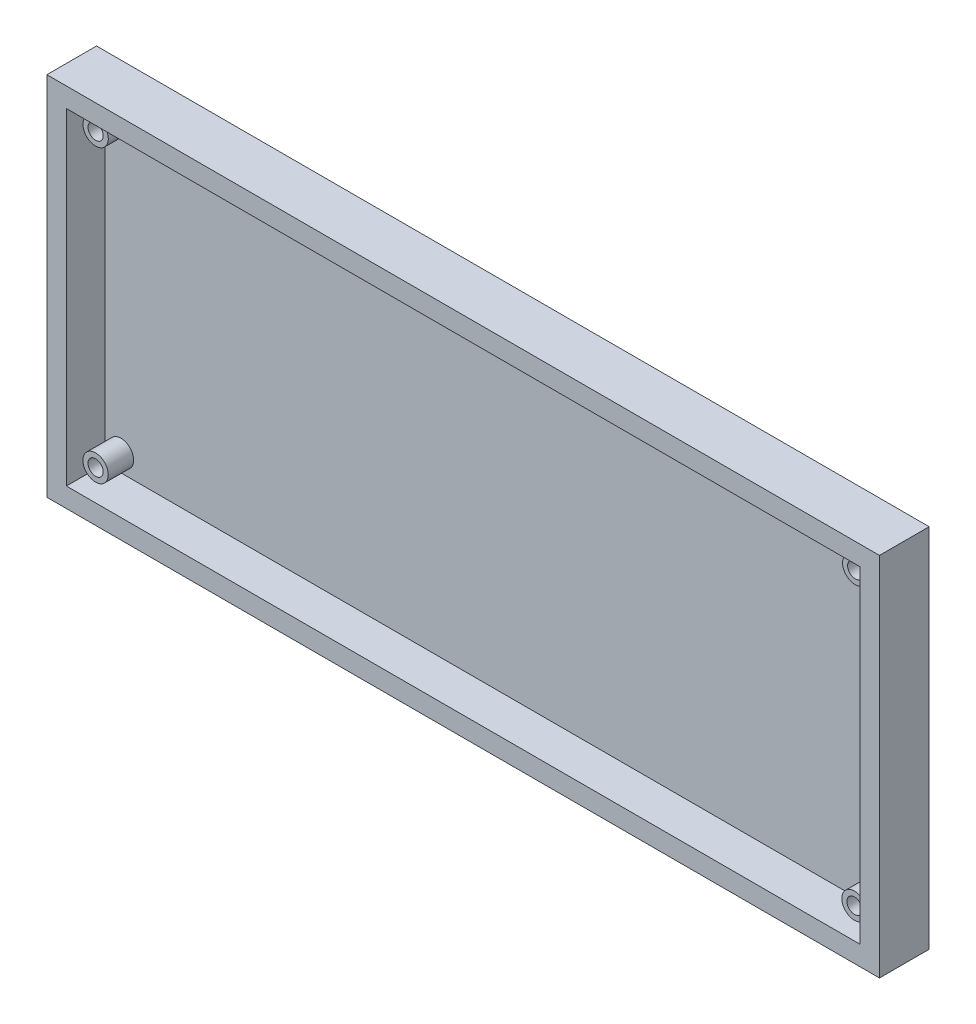
SolidWorks part; units mm, degrees
ref_plane "Front Plane" through (0, 0, 0) normal (0, 0, 1) x (1, 0, 0)
ref_plane "Top Plane" through (0, 0, 0) normal (0, 1, 0) x (1, 0, 0)
ref_plane "Right Plane" through (0, 0, 0) normal (1, 0, 0) x (0, 0, -1)
sketch "Sketch1" plane through (0, 0, 0) normal (0, 0, 1) x (1, 0, 0)
  line L0 (-3.6744, 71.2234) -> (-8.1645, 75.7135) construction
  line L1 (-3.6744, 71.2234) -> (178.9008, 71.2234)
  line L2 (-3.6744, 71.2234) -> (-3.6744, -4)
  line L3 (-3.6744, -4) -> (178.9008, -4)
  line L4 (178.9008, 71.2234) -> (178.9008, -4)
  line L5 (178.9008, -4) -> (183.3909, -8.4901) construction
  line L7 (-8.1645, 75.7135) -> (183.3909, 75.7135)
  line L8 (-8.1645, 75.7135) -> (-8.1645, -8.4901)
  line L9 (-8.1645, -8.4901) -> (183.3909, -8.4901)
  line L10 (183.3909, 75.7135) -> (183.3909, -8.4901)
  dimension "D1" = 178.9008
  dimension "D2" = 3.6744
  dimension "D3" = 71.2234
  dimension "D4" = 4
  dimension "D5" = 6.35
extrude "Boss-Extrude1" add sketch "Sketch1" along normal blind 2.54 and the other way blind 8.89
sketch "Sketch3" plane through (0, 0, -8.89) normal (0, 0, -1) x (-1, 0, 0)
  line L1 (-178.9008, 71.2234) -> (3.6744, 71.2234)
  line L2 (-178.9008, 71.2234) -> (-178.9008, -4)
  line L3 (-178.9008, -4) -> (3.6744, -4)
  line L4 (3.6744, 71.2234) -> (3.6744, -4)
extrude "Boss-Extrude4" add sketch "Sketch3" against normal blind 2.54
sketch "Sketch4" plane through (0, 0, -6.35) normal (0, 0, 1) x (1, 0, 0)
  line L0 (178.9008, 71.2234) -> (178.9008, -4) construction
  line L1 (-3.6744, 71.2234) -> (178.9008, 71.2234) construction
  circle A0 centre (0.0086, 66.9562) radius 1.75
  circle A1 centre (0.0086, 66.9562) radius 2.915
  circle A2 centre (174.7606, 66.9562) radius 1.75
  circle A3 centre (174.7606, 66.9562) radius 2.915
  circle A4 centre (174.6, 0) radius 1.75
  circle A5 centre (174.6, 0) radius 2.915
  circle A6 centre (0, 0) radius 1.75
  circle A7 centre (0, 0) radius 2.915
  point P4 (174.7606, 66.9562)
  point P12 (174.6, 0)
  point P17 (0, 0)
  dimension "D1" = 3.5
  dimension "D2" = 3.5
extrude "Boss-Extrude6" add sketch "Sketch4" along normal blind 5.842
